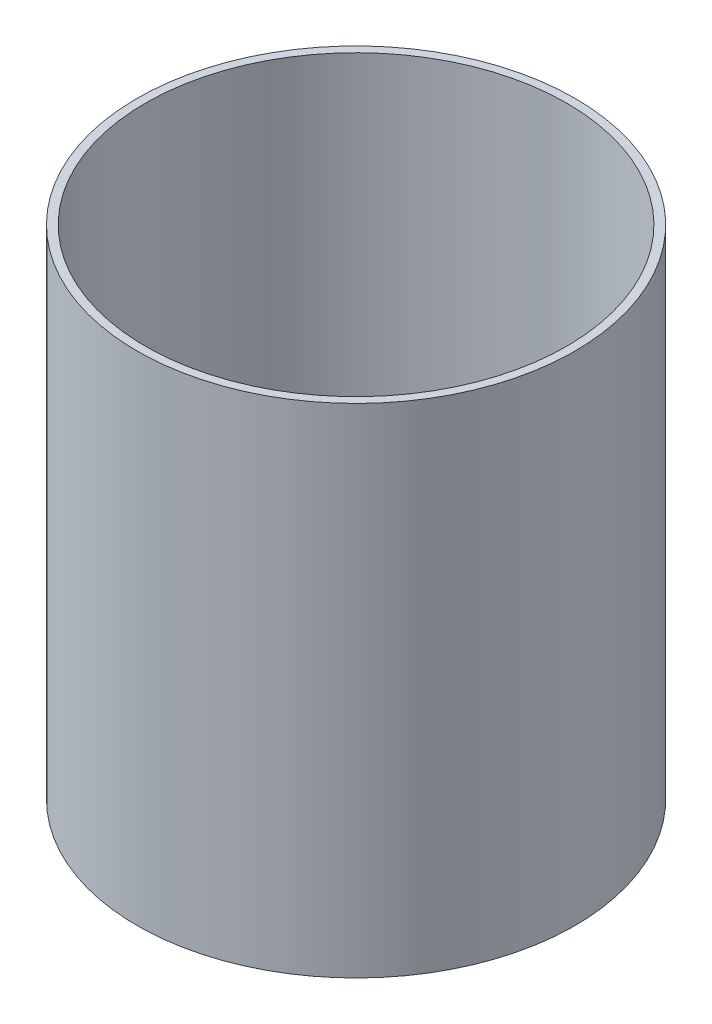
SolidWorks part; units mm, degrees
ref_plane "Front Plane" through (0, 0, 0) normal (0, 0, 1) x (1, 0, 0)
ref_plane "Top Plane" through (0, 0, 0) normal (0, 1, 0) x (1, 0, 0)
ref_plane "Right Plane" through (0, 0, 0) normal (1, 0, 0) x (0, 0, -1)
sketch "Sketch1" plane through (0, 0, 0) normal (0, 1, 0) x (1, 0, 0)
  circle A0 centre (0, 0) radius 39.6
  circle A1 centre (0, 0) radius 38.1
  dimension "D1" = 79.2
  dimension "D2" = 76.2
extrude "Boss-Extrude1" add sketch "Sketch1" along normal blind 90
